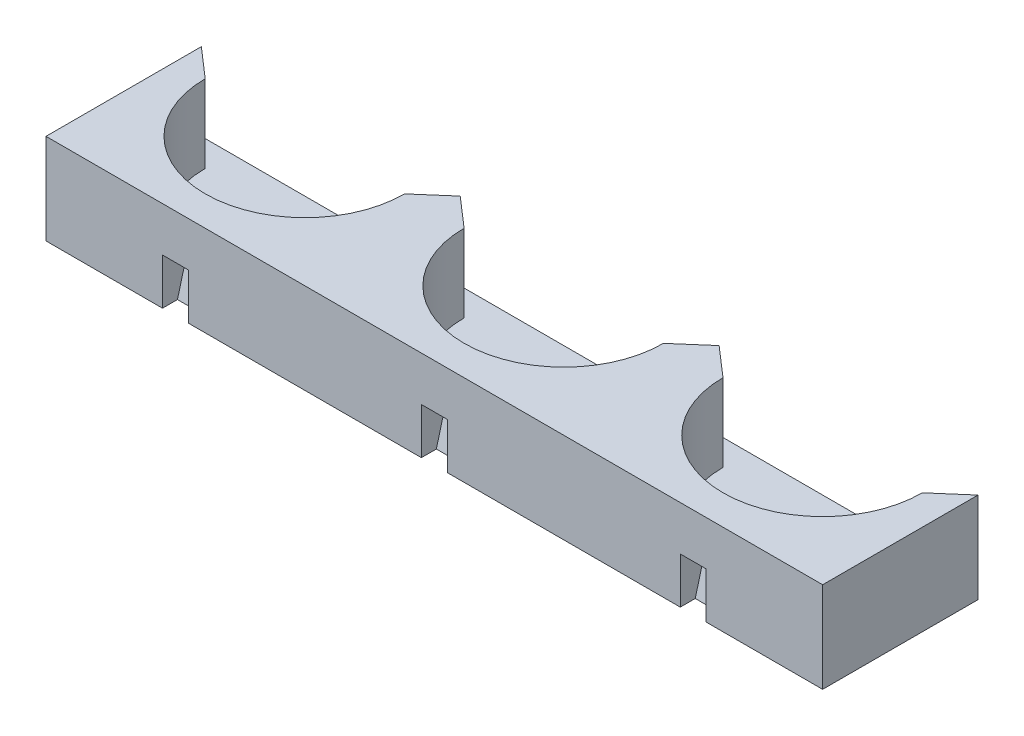
SolidWorks part; units mm, degrees
ref_plane "Plan de face" through (0, 0, 0) normal (0, 0, 1) x (1, 0, 0)
ref_plane "Plan de dessus" through (0, 0, 0) normal (0, 1, 0) x (1, 0, 0)
ref_plane "Plan de droite" through (0, 0, 0) normal (1, 0, 0) x (0, 0, -1)
sketch "Esquisse1" plane through (0, 0, 0) normal (0, 1, 0) x (1, 0, 0)
  line L4 (0, 0) -> (300, 0)
  line L5 (0, 0) -> (0, 60)
  line L6 (300, 0) -> (300, 60)
  line L7 (150, 0) -> (150, 113.7851) construction
  line L8 (50, 50) -> (150, 50) construction
  line L9 (11.5, 50) -> (0, 60)
  line L10 (111.5, 50) -> (100, 60)
  line L11 (100, 60) -> (88.5, 50)
  line L12 (188.5, 50) -> (200, 60)
  line L13 (200, 60) -> (211.5, 50)
  line L14 (288.5, 50) -> (300, 60)
  arc A0 (11.5, 50) -> (88.5, 50) centre (50, 50) ccw
  arc A1 (111.5, 50) -> (188.5, 50) centre (150, 50) ccw
  arc A2 (288.5, 50) -> (211.5, 50) centre (250, 50) cw
  point P20 (150, 11.5)
  dimension "D2" = 38.5
  dimension "D1" = 300
  dimension "D3" = 60
  dimension "D4" = 100
  dimension "D5" = 50
  dimension "D6" = 38.5
extrude "Boss.-Extru.1" add sketch "Esquisse1" along normal blind 30
sketch "Esquisse2" plane through (0, 0, 0) normal (0, -1, 0) x (1, 0, 0)
  line L1 (300, -60) -> (0, -60)
  line L2 (300, -60) -> (300, 0)
  line L3 (300, 0) -> (0, 0)
  line L4 (0, -60) -> (0, 0)
extrude "Boss.-Extru.2" add sketch "Esquisse2" along normal blind 5
sketch "Esquisse3" plane through (0, -5, 0) normal (0, -1, 0) x (1, 0, 0)
  line L0 (150, 0) -> (150, -98.443) construction
  line L1 (300, 0) -> (0, 0) construction
  line L2 (45, -5.78) -> (55, -5.78)
  line L3 (255, 0) -> (245, 0)
  line L4 (255, 0) -> (255, -5.78)
  line L5 (255, -5.78) -> (245, -5.78)
  line L6 (245, 0) -> (245, -5.78)
  line L7 (55, 0) -> (55, -5.78)
  line L8 (45, 0) -> (55, 0)
  line L9 (45, 0) -> (45, -5.78)
  line L11 (155, 0) -> (145, 0)
  line L12 (155, 0) -> (155, -5.78)
  line L13 (155, -5.78) -> (145, -5.78)
  line L14 (145, 0) -> (145, -5.78)
  point P8 (250, 0)
  point P17 (150, 0)
  dimension "D1" = 100
  dimension "D2" = 10
  dimension "D3" = 5.78
  dimension "D4" = 10
  dimension "D5" = 5.78
sketch "Esquisse4" plane through (0, 0, 0) normal (-1, 0, 0) x (0, 0, 1)
  line L0 (0, -5) -> (-7.2909, 22.21) construction
  line L1 (0, 30) -> (0, -5) construction
  dimension "D1" = 15
extrude "Enlèv. mat.-Extru.3" cut sketch "Esquisse3" along direction (0, 0.9659, -0.2588) on the side against the normal blind 14.49
sketch "Esquisse5" plane through (0, 0, 0) normal (0, 0, 1) x (1, 0, 0)
  line L0 (255, -5) -> (245, -5)
  line L1 (255, -5) -> (255, 12.8)
  line L2 (245, -5) -> (245, 12.8)
  line L3 (255, 12.8) -> (245, 12.8)
  line L4 (155, -5) -> (145, -5)
  line L5 (155, -5) -> (155, 12.8)
  line L6 (145, -5) -> (145, 12.8)
  line L7 (155, 12.8) -> (145, 12.8)
  line L8 (55, -5) -> (45, -5)
  line L9 (55, -5) -> (55, 12.8)
  line L10 (45, -5) -> (45, 12.8)
  line L11 (55, 12.8) -> (45, 12.8)
  dimension "D1" = 17.8
extrude "Enlèv. mat.-Extru.5" cut sketch "Esquisse5" against normal blind 5
sketch "Esquisse7" plane through (55, 0, 0) normal (-1, 0, 0) x (0, 0, 1)
  line L0 (-9.5303, 8.9963) -> (0, 12.8) construction
  line L1 (0, 12.8) -> (-9.5303, 12.8) construction
  line L2 (-9.5303, 8.9963) -> (-9.5303, 12.8) construction
  line L3 (-9.5303, 8.9963) -> (0, 12.8)
  line L4 (0, 12.8) -> (-9.5303, 12.8)
  line L5 (-9.5303, 12.8) -> (-9.5303, 8.9963)
extrude "Boss.-Extru.4" add sketch "Esquisse7" along normal up to next
sketch "Esquisse8" plane through (55, 0, 0) normal (-1, 0, 0) x (0, 0, 1)
  line L0 (-9.5303, 8.9963) -> (0, 12.8)
  line L1 (0, 12.8) -> (0, -5)
  line L2 (0, -5) -> (-5.78, -5)
  line L3 (-5.78, -5) -> (-9.5303, 8.9963)
extrude "Enlèv. mat.-Extru.6" cut sketch "Esquisse8" along normal blind 10
pattern_linear "Répétition linéaire1" count 3 spacing 100 along (1, 0, 0) of "Boss.-Extru.4", "Enlèv. mat.-Extru.6"
